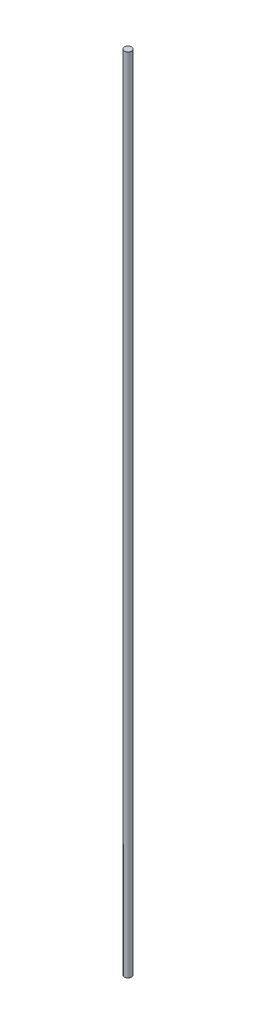
SolidWorks part; units mm, degrees
material "AISI 304"
ref_plane "Plan de face" through (0, 0, 0) normal (0, 0, 1) x (1, 0, 0)
ref_plane "Plan de dessus" through (0, 0, 0) normal (0, 1, 0) x (1, 0, 0)
ref_plane "Plan de droite" through (0, 0, 0) normal (1, 0, 0) x (0, 0, -1)
sketch "Sketch1" plane through (0, 0, 0) normal (0, 1, 0) x (1, 0, 0)
  circle A0 centre (0, 0) radius 5
  dimension "D1" = 10
extrude "Boss-Extrude1" add sketch "Sketch1" along normal blind 1100
